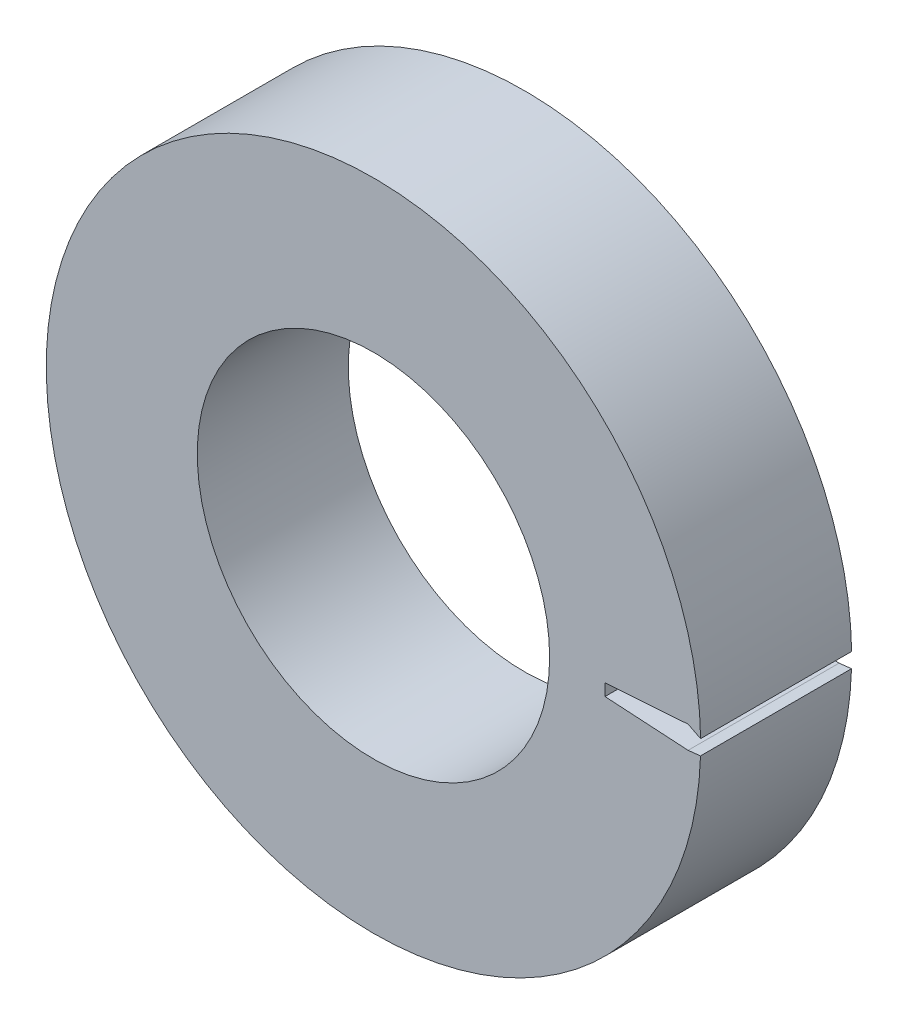
SolidWorks part; units mm, degrees
ref_plane "Спереди" through (0, 0, 0) normal (0, 0, 1) x (1, 0, 0)
ref_plane "Сверху" through (0, 0, 0) normal (0, 1, 0) x (1, 0, 0)
ref_plane "Справа" through (0, 0, 0) normal (1, 0, 0) x (0, 0, -1)
sketch "Эскиз1" plane through (0, 0, 0) normal (0, 0, 1) x (1, 0, 0)
  circle A0 centre (0, 0) radius 65
  circle A1 centre (0, 0) radius 35
extrude "Stator_blank" add sketch "Эскиз1" along normal mid plane 30
sketch "Эскиз2" plane through (0, 0, 0) normal (0, 0, 1) x (1, 0, 0)
  line L0 (46, -1.25) -> (62.5, -2.25)
  line L1 (62.5, -2.25) -> (67, -1.75)
  line L2 (67, -1.75) -> (67, 0)
  line L3 (67, 0) -> (62.5, 2.25)
  line L4 (62.5, 2.25) -> (46, 1.125)
  line L5 (46, 1.125) -> (46, -1.25)
extrude "Slot_cut_test" cut sketch "Эскиз2" against normal mid plane 40
